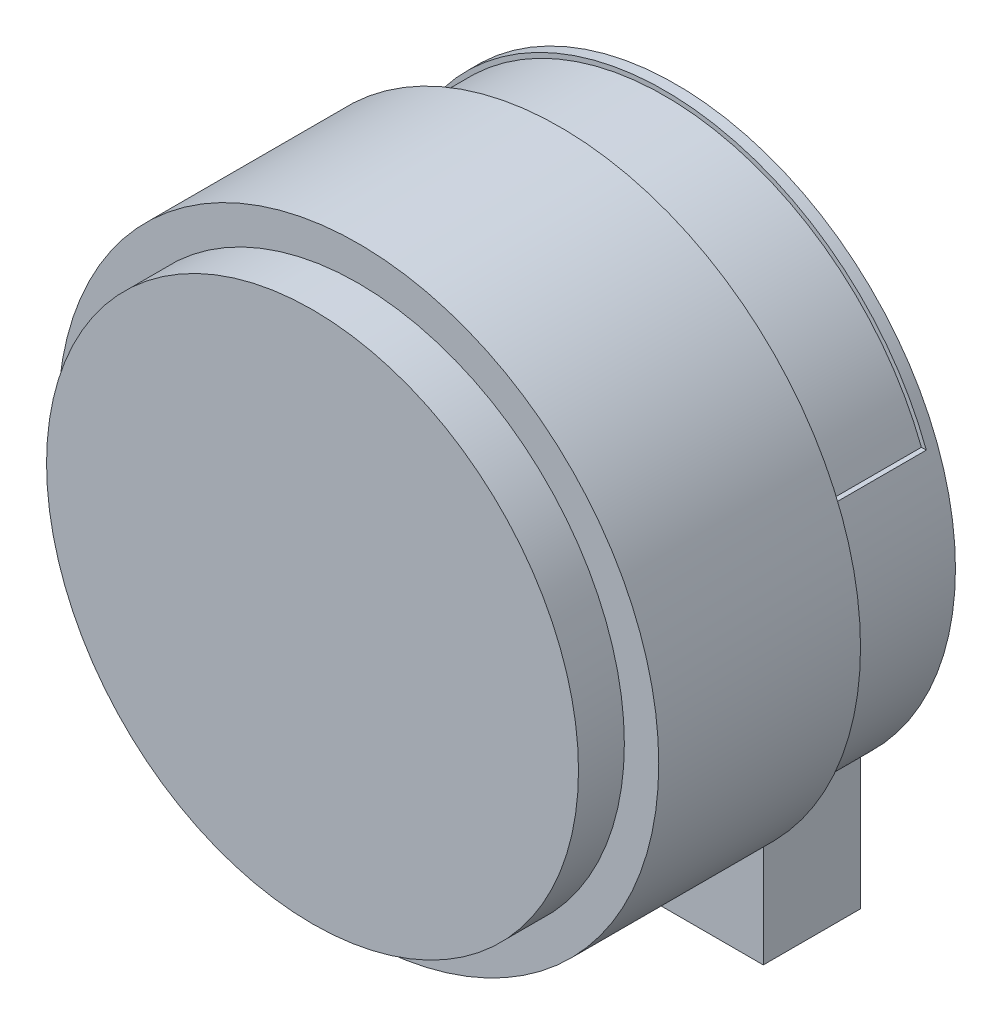
SolidWorks part; units mm, degrees
ref_plane "前视基准面" through (0, 0, 0) normal (0, 0, 1) x (1, 0, 0)
ref_plane "上视基准面" through (0, 0, 0) normal (0, 1, 0) x (1, 0, 0)
ref_plane "右视基准面" through (0, 0, 0) normal (1, 0, 0) x (0, 0, -1)
sketch "草图1" plane through (0, 0, 0) normal (0, 0, 1) x (1, 0, 0)
  circle A0 centre (0, 0) radius 30.5
  dimension "D1" = 61
extrude "凸台-拉伸1" add sketch "草图1" along normal blind 12.6
sketch "草图2" plane through (0, 0, 12.6) normal (0, 0, 1) x (1, 0, 0)
  circle A0 centre (0, 0) radius 32.75
  dimension "D1" = 65.5
extrude "凸台-拉伸2" add sketch "草图2" along normal blind 22
sketch "草图3" plane through (0, 0, 34.6) normal (0, 0, 1) x (1, 0, 0)
  circle A0 centre (0, 0) radius 29
  dimension "D1" = 58
extrude "凸台-拉伸3" add sketch "草图3" along normal blind 5
sketch "草图4" plane through (0, 0, 0) normal (0, 0, -1) x (-1, 0, 0)
  line L0 (0, 0) -> (0, -49.964) construction
  line L2 (-21.25, -21.8789) -> (21.25, -21.8789)
  line L3 (-21.25, -21.8789) -> (-21.25, -36.2)
  line L4 (-21.25, -36.2) -> (21.25, -36.2)
  line L5 (21.25, -21.8789) -> (21.25, -36.2)
  line L6 (-21.25, -21.8789) -> (21.25, -36.2) construction
  line L7 (-21.25, -36.2) -> (21.25, -21.8789) construction
  circle A0 centre (0, 0) radius 30.5 construction
  point P3 (0, -29.0395)
  point P8 (21.25, -21.8789)
  circle M5 centre (0, 0) radius 30.5
  dimension "D1" = 42.5
  dimension "D2" = 36.2
extrude "凸台-拉伸4" add sketch "草图4" against normal blind 10.6 from offset 1.1 contours L5 L3 L4 M5 offset against normal yes
sketch "草图5" plane through (0, -36.2, 0) normal (0, -1, 0) x (1, 0, 0)
  line L0 (-21.25, 6.4) -> (21.25, 6.4) construction
  line L1 (-21.25, 11.7) -> (-21.25, 1.1) construction
  line L2 (21.25, 11.7) -> (21.25, 1.1) construction
  line L3 (0, 11.7) -> (0, 6.4) construction
  line L4 (21.25, 11.7) -> (-21.25, 11.7) construction
  circle A0 centre (-18, 6.4) radius 1.5
  circle A1 centre (18, 6.4) radius 1.5
  dimension "D1" = 3
  dimension "D2" = 36
extrude "切除-拉伸1" cut sketch "草图5" against normal blind 5
sketch "草图6" plane through (0, 0, 0) normal (0, 0, -1) x (-1, 0, 0)
  circle A0 centre (0, 0) radius 27.75
  dimension "D1" = 55.5
extrude "切除-拉伸2" cut sketch "草图6" against normal blind 2
sketch "草图7" plane through (0, 0, 0) normal (0, 0, -1) x (-1, 0, 0)
  line L0 (-28.5238, 10.8) -> (28.5238, 10.8)
  line L1 (-21.25, -36.2) -> (21.25, -36.2) construction
  circle A0 centre (0, 0) radius 30
  circle A2 centre (0, 0) radius 30.5 construction
  circle A3 centre (0, 0) radius 30.5
  circle A4 centre (0, 0) radius 30.5 construction
  point P10 (-28.5238, 10.8)
  point P13 (28.5238, 10.8)
  point P14 (28.5238, 10.8)
  point P15 (28.5238, 10.8)
  circle M5 centre (0, 0) radius 30.5
  dimension "D1" = 0.5
  dimension "D2" = 47
extrude "切除-拉伸3" cut sketch "草图7" against normal blind 10.8 from offset 1.2 contours A0 L0 M5 | A3
